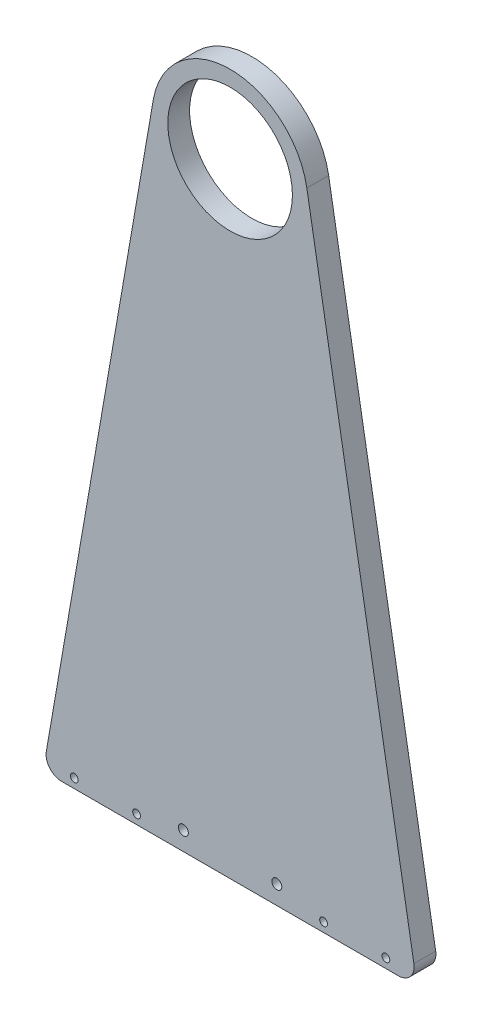
SolidWorks part; units mm, degrees
material "7075-T6，板材(SS)"
ref_plane "前视基准面" through (0, 0, 0) normal (0, 0, 1) x (1, 0, 0)
ref_plane "上视基准面" through (0, 0, 0) normal (0, 1, 0) x (1, 0, 0)
ref_plane "右视基准面" through (0, 0, 0) normal (1, 0, 0) x (0, 0, -1)
sketch "草图1" plane through (0, 0, 0) normal (0, 0, 1) x (1, 0, 0)
  line L0 (0, 0) -> (0, -200) construction
  line L1 (-60, -200) -> (60, -200)
  line L2 (24.6335, 4.2651) -> (60, -200)
  line L3 (-24.6335, 4.2651) -> (-60, -200)
  circle A0 centre (0, 0) radius 21 construction
  circle A1 centre (0, 0) radius 25 construction
  arc A2 (-24.6335, 4.2651) -> (24.6335, 4.2651) centre (0, 0) cw
  point P5 (-24.6335, 4.2651)
  point P8 (0, -200)
  point P10 (-24.6335, 4.2651)
  point P12 (24.6335, 4.2651)
  dimension "D1" = 42
  dimension "D2" = 50
  dimension "D3" = 200
  dimension "D4" = 207.3041
  dimension "D5" = 120
extrude "凸台-拉伸1" add sketch "草图1" along normal blind 7 contours A2 L3 L1 L2
sketch "草图2" plane through (0, 0, 7) normal (0, 0, 1) x (1, 0, 0)
  circle A0 centre (0, 0) radius 20
  dimension "D1" = 40
extrude "切除-拉伸1" cut sketch "草图2" against normal blind 7
sketch "草图3" plane through (0, 0, 7) normal (0, 0, 1) x (1, 0, 0)
  line L0 (-45.8849, -194) -> (49954.1151, -194) construction
  line L1 (-60, -200) -> (60, -200) construction
  line L2 (-24.6335, 4.2651) -> (-60, -200) construction
  line L3 (24.6335, 4.2651) -> (60, -200) construction
  circle A0 centre (-15.0017, -194) radius 1.6
  circle A1 centre (14.9983, -194) radius 1.6
  dimension "D2" = 3.2
  dimension "D3" = 30
  dimension "D5" = 43.3184
  dimension "D1" = 6
  dimension "D4" = 43.315
extrude "切除-拉伸2" cut sketch "草图3" against normal blind 7
cosmetic thread "装饰螺纹线1" parameters "D2"=4
cosmetic thread "装饰螺纹线2" parameters "D2"=4
fillet "圆角1" radius 5 2 edges at (60, -200, 3.5) (-60, -200, 3.5)
sketch "草图4" plane through (0, 0, 7) normal (0, 0, 1) x (1, 0, 0)
  line L0 (-32.4528, -197) -> (49967.5472, -197) construction
  line L1 (-54.0599, -200) -> (54.0599, -200) construction
  line L2 (0, -1000) -> (0, 49000) construction
  circle A0 centre (-50.0017, -197) radius 1.25
  circle A1 centre (-30.0017, -197) radius 1.25
  circle A2 centre (-15.0017, -194) radius 1.6 construction
  circle A3 centre (30.0017, -197) radius 1.25
  circle A4 centre (50.0017, -197) radius 1.25
  dimension "D2" = 2.5
  dimension "D3" = 20
  dimension "D4" = 15
  dimension "D1" = 3
extrude "切除-拉伸3" cut sketch "草图4" against normal blind 10
cosmetic thread "装饰螺纹线3" parameters "D2"=3
cosmetic thread "装饰螺纹线4" parameters "D2"=3
cosmetic thread "装饰螺纹线5" parameters "D2"=3
cosmetic thread "装饰螺纹线6" parameters "D2"=3
